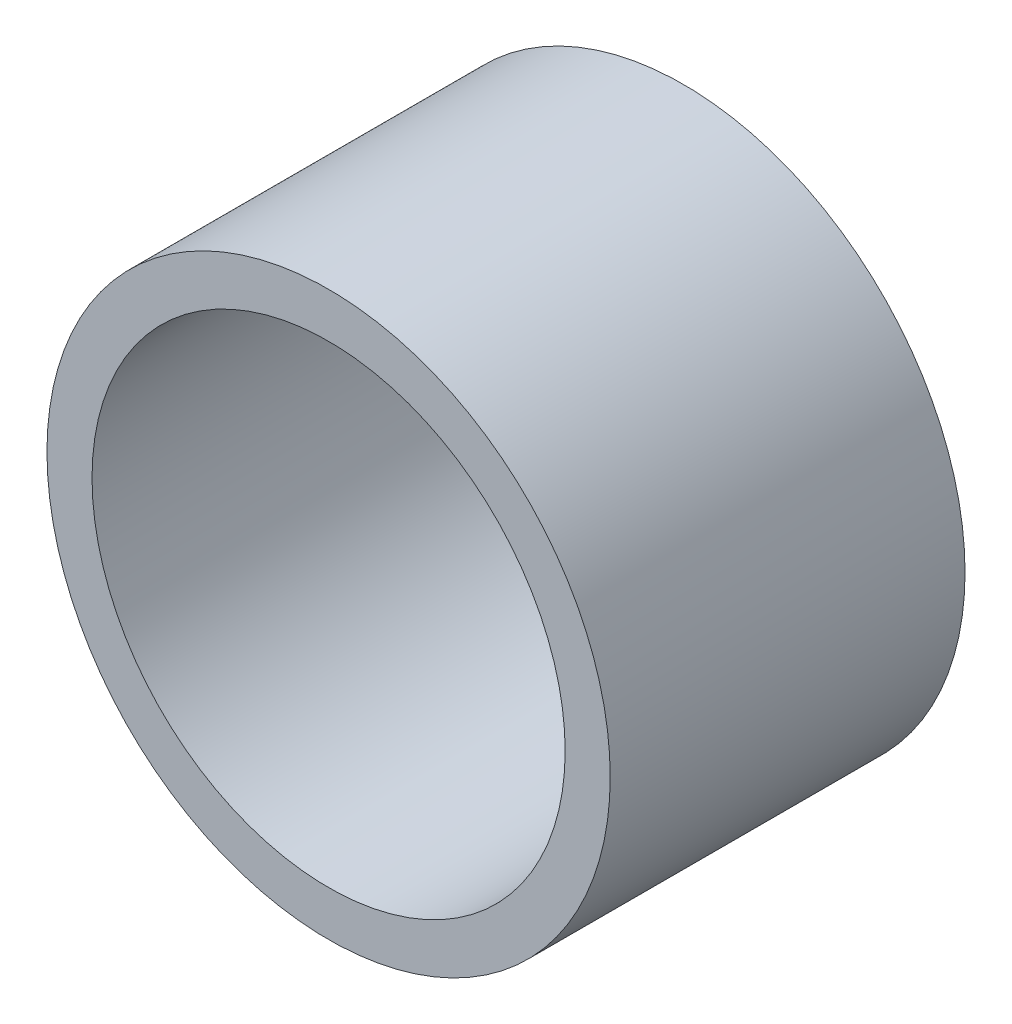
SolidWorks part; units mm, degrees
material "6061-T6 (SS)"
ref_plane "Front Plane" through (0, 0, 0) normal (0, 0, 1) x (1, 0, 0)
ref_plane "Top Plane" through (0, 0, 0) normal (0, 1, 0) x (1, 0, 0)
ref_plane "Right Plane" through (0, 0, 0) normal (1, 0, 0) x (0, 0, -1)
sketch "Sketch1" plane through (0, 0, 0) normal (0, 0, 1) x (1, 0, 0)
  circle A0 centre (0, 0) radius 3.175
  circle A1 centre (0, 0) radius 2.667
  dimension "D1" = 6.35
  dimension "D2" = 0.508
extrude "Boss-Extrude1" add sketch "Sketch1" along normal blind 4
